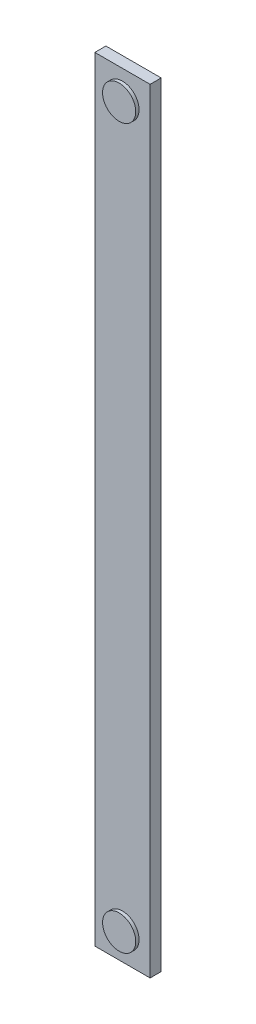
SolidWorks part; units mm, degrees
material "Plain Carbon Steel"
ref_plane "Front Plane" through (0, 0, 0) normal (0, 0, 1) x (1, 0, 0)
ref_plane "Top Plane" through (0, 0, 0) normal (0, 1, 0) x (1, 0, 0)
ref_plane "Right Plane" through (0, 0, 0) normal (1, 0, 0) x (0, 0, -1)
sketch "Sketch1" plane through (0, 0, 0) normal (0, 0, 1) x (1, 0, 0)
  line L1 (-25, 350) -> (25, 350)
  line L2 (-25, 350) -> (-25, -350)
  line L3 (-25, -350) -> (25, -350)
  line L4 (25, 350) -> (25, -350)
  line L5 (-25, 350) -> (25, -350) construction
  line L6 (-25, -350) -> (25, 350) construction
  point P0 (0, 0)
  dimension "D1" = 50
  dimension "D2" = 700
extrude "Boss-Extrude1" add sketch "Sketch1" along normal mid plane 10
sketch "Sketch2" plane through (0, 0, 5) normal (0, 0, 1) x (1, 0, 0)
  line L0 (-25, -350) -> (25, -350) construction
  line L1 (25, 350) -> (-25, 350) construction
  circle A0 centre (0, -325) radius 15
  circle A1 centre (0, 325) radius 15
  dimension "D1" = 25
  dimension "D2" = 30
  dimension "D3" = 25
  dimension "D4" = 30
extrude "Boss-Extrude2" add sketch "Sketch2" along normal blind 3
